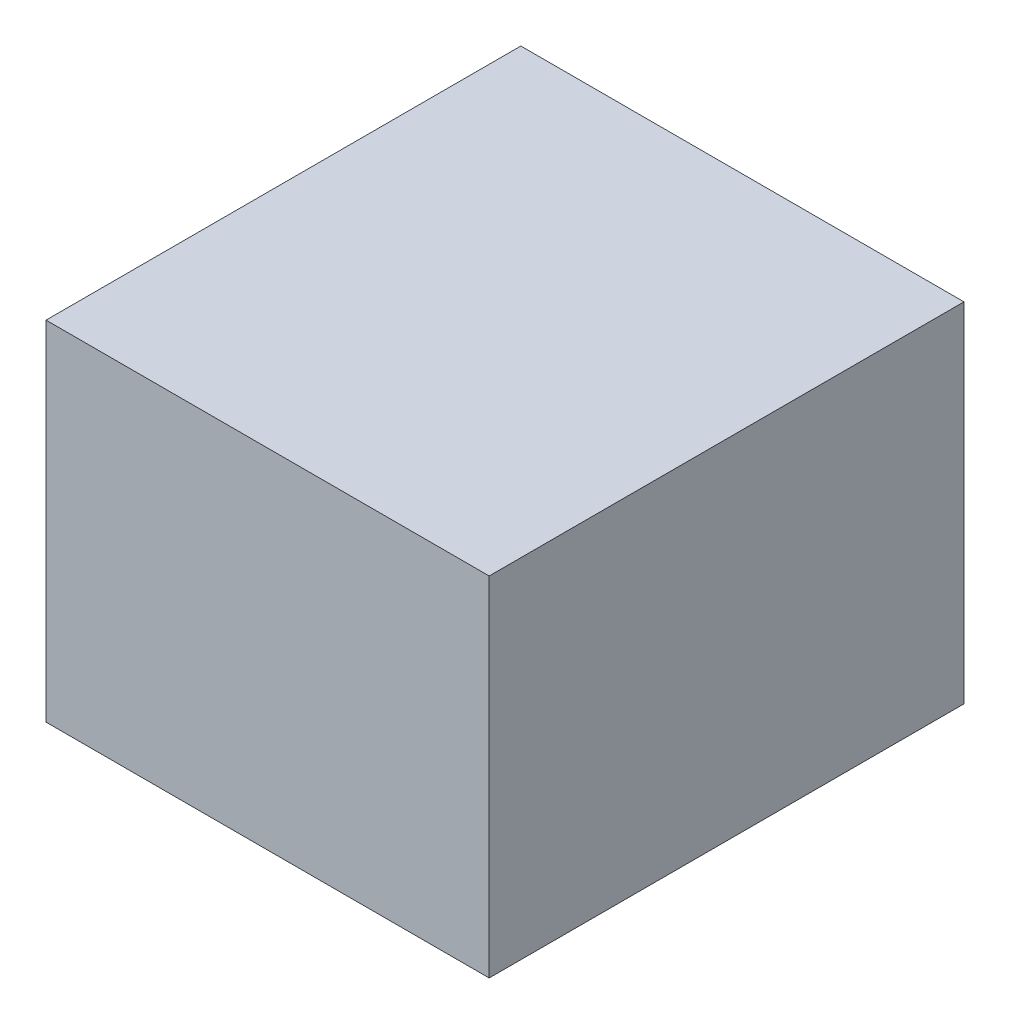
SolidWorks part; units mm, degrees
material "ABS"
ref_plane "Alzado" through (0, 0, 0) normal (0, 0, 1) x (1, 0, 0)
ref_plane "Planta" through (0, 0, 0) normal (0, 1, 0) x (1, 0, 0)
ref_plane "Vista lateral" through (0, 0, 0) normal (1, 0, 0) x (0, 0, -1)
sketch "Croquis1" plane through (0, 0, 0) normal (0, 0, 1) x (1, 0, 0)
  line L1 (-14, 11) -> (14, 11)
  line L2 (-14, 11) -> (-14, -11)
  line L3 (-14, -11) -> (14, -11)
  line L4 (14, 11) -> (14, -11)
  line L5 (-14, 11) -> (14, -11) construction
  line L6 (-14, -11) -> (14, 11) construction
  point P0 (0, 0)
  dimension "D1" = 22
  dimension "D2" = 28
extrude "Saliente-Extruir1" add sketch "Croquis1" along normal mid plane 30
